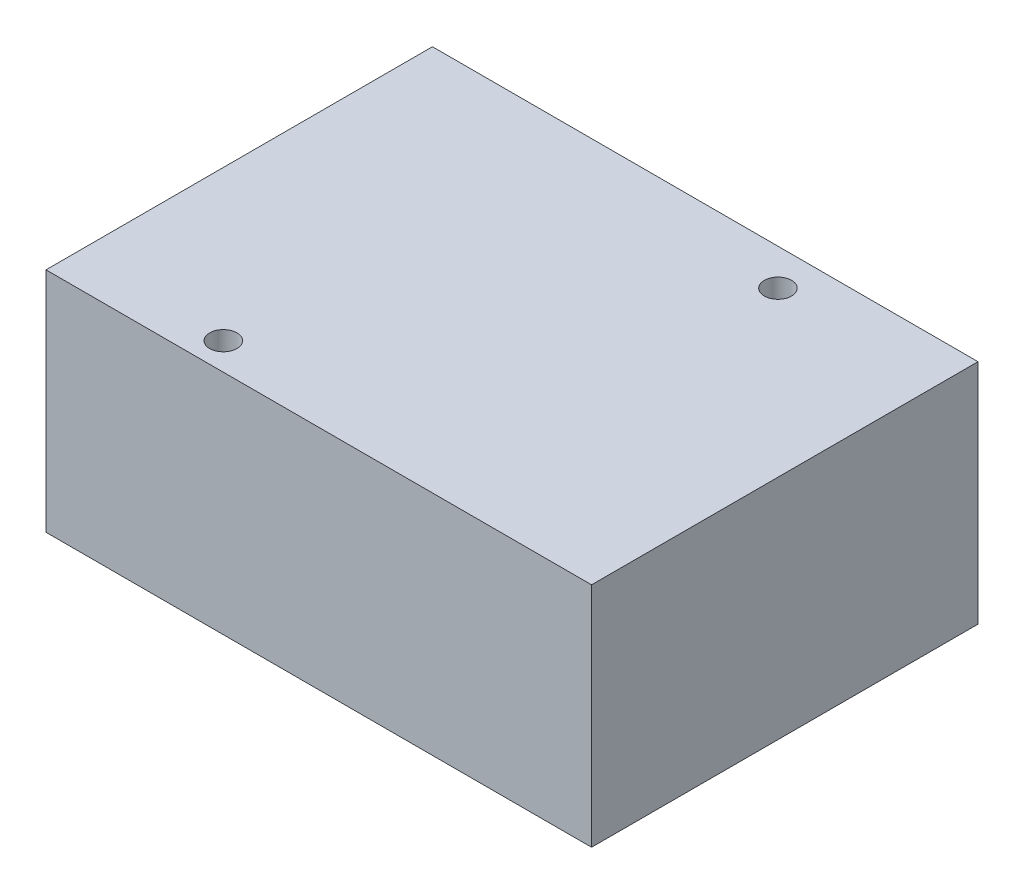
SolidWorks part; units mm, degrees
ref_plane "Front Plane" through (0, 0, 0) normal (0, 0, 1) x (1, 0, 0)
ref_plane "Top Plane" through (0, 0, 0) normal (0, 1, 0) x (1, 0, 0)
ref_plane "Right Plane" through (0, 0, 0) normal (1, 0, 0) x (0, 0, -1)
sketch "Sketch1" plane through (0, 0, 0) normal (0, 1, 0) x (1, 0, 0)
  line L1 (-30, 21.25) -> (30, 21.25)
  line L2 (-30, 21.25) -> (-30, -21.25)
  line L3 (-30, -21.25) -> (30, -21.25)
  line L4 (30, 21.25) -> (30, -21.25)
  line L5 (-30, 21.25) -> (30, -21.25) construction
  line L6 (-30, -21.25) -> (30, 21.25) construction
  point P0 (0, 0)
  dimension "D1" = 60
  dimension "D2" = 42.5
extrude "Boss-Extrude1" add sketch "Sketch1" along normal blind 25
sketch "Sketch2" plane through (0, 25, 0) normal (0, 1, 0) x (1, 0, 0)
  line L0 (12, 17.25) -> (12, 21.25) construction
  line L1 (30, 21.25) -> (-30, 21.25) construction
  line L2 (12, 17.25) -> (30, 17.25) construction
  line L3 (30, -21.25) -> (30, 21.25) construction
  line L4 (-13.5, -18.25) -> (-13.5, -21.25) construction
  line L5 (-30, -21.25) -> (30, -21.25) construction
  line L6 (-13.5, -18.25) -> (-30, -18.25) construction
  line L7 (-30, 21.25) -> (-30, -21.25) construction
  circle A0 centre (12, 17.25) radius 1.5
  circle A1 centre (-13.5, -18.25) radius 1.5
  dimension "D3" = 3
  dimension "D1" = 4
  dimension "D2" = 18
  dimension "D4" = 3
  dimension "D5" = 16.5
extrude "Cut-Extrude1" cut sketch "Sketch2" against normal through all
